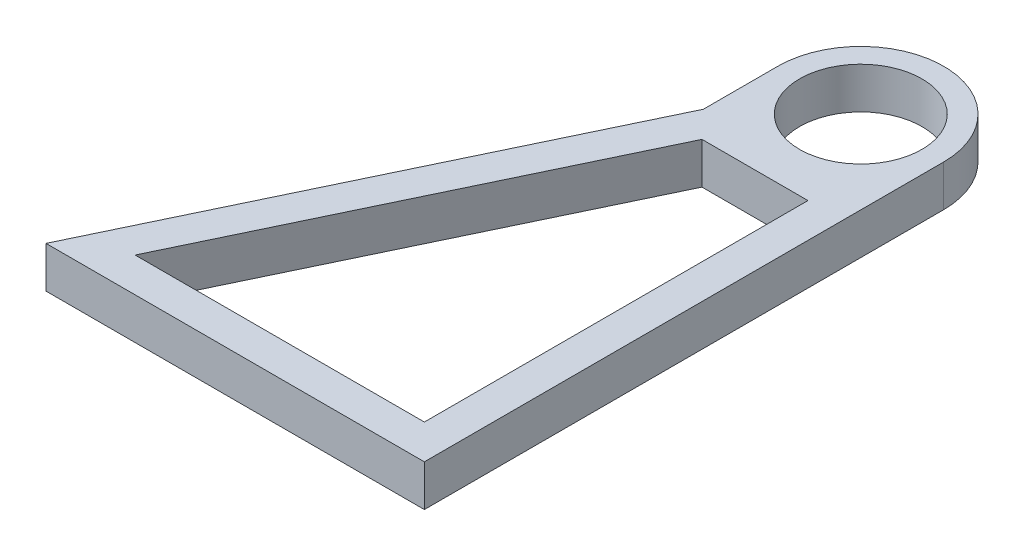
SolidWorks part; units mm, degrees
ref_plane "Front Plane" through (0, 0, 0) normal (0, 0, 1) x (1, 0, 0)
ref_plane "Top Plane" through (0, 0, 0) normal (0, 1, 0) x (1, 0, 0)
ref_plane "Right Plane" through (0, 0, 0) normal (1, 0, 0) x (0, 0, -1)
sketch "Sketch1" plane through (0, 0, 0) normal (0, 1, 0) x (1, 0, 0)
  line L2 (-85.725, -150.6925) -> (24.0626, -150.6925)
  line L4 (-85.725, -150.6925) -> (-24.0626, -21.6195)
  line L5 (-24.0626, -21.6195) -> (-24.0626, 0)
  line L6 (24.0626, -150.6925) -> (24.0626, 0)
  circle A0 centre (0, 0) radius 17.75
  arc A1 (24.0626, 0) -> (-24.0626, 0) centre (0, 0) ccw
  point P12 (-85.725, -150.6925)
  dimension "D1" = 35.5
extrude "Boss-Extrude1" add sketch "Sketch1" along normal blind 12
sketch "Sketch3" plane through (0, 0, 0) normal (0, -1, 0) x (1, 0, 0)
  line L0 (14.0626, 46.3229) -> (14.0626, 29.3843)
  line L1 (14.0626, 29.3843) -> (-16.6896, 29.3843)
  line L5 (-69.8651, 140.6925) -> (-14.0626, 23.8855)
  line L6 (-69.8651, 140.6925) -> (-16.6896, 29.3843)
  line L7 (-14.0626, 23.8855) -> (-14.0626, 0)
  line L10 (14.0626, 0) -> (14.0626, 140.6925)
  line L11 (14.0626, 140.6925) -> (-69.8651, 140.6925)
  line L14 (14.0626, 46.3229) -> (14.0626, 140.6925)
  line L15 (14.0626, 140.6925) -> (-69.8651, 140.6925)
  arc A1 (-14.0626, 0) -> (14.0626, 0) centre (0, 0) ccw
  dimension "D1" = 10
extrude "Cut-Extrude1" cut sketch "Sketch3" against normal blind 37
